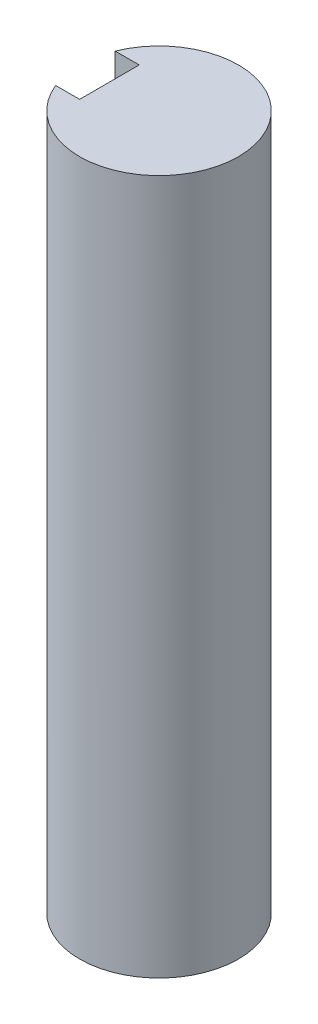
SolidWorks part; units mm, degrees
ref_plane "Front Plane" through (0, 0, 0) normal (0, 0, 1) x (1, 0, 0)
ref_plane "Top Plane" through (0, 0, 0) normal (0, 1, 0) x (1, 0, 0)
ref_plane "Right Plane" through (0, 0, 0) normal (1, 0, 0) x (0, 0, -1)
sketch "Sketch1" plane through (0, 0, 0) normal (0, 1, 0) x (1, 0, 0)
  circle A0 centre (0, 0) radius 4
  dimension "D1" = 8
extrude "Boss-Extrude1" add sketch "Sketch1" along normal blind 35
sketch "Sketch2" plane through (0, 0, 0) normal (0, -1, 0) x (1, 0, 0)
  line L0 (0, -2.5) -> (0, 2) construction
  line L1 (-1.5, 2) -> (1.5, 2)
  arc A0 (-1.5, 2) -> (1.5, 2) centre (0, 0) ccw
  dimension "D1" = 5
  dimension "D2" = 4.5
extrude "Cut-Extrude1" cut sketch "Sketch2" against normal blind 22
sketch "Sketch3" plane through (0, 0, 0) normal (0, -1, 0) x (1, 0, 0)
  circle A0 centre (0, 0) radius 2.5
  dimension "D1" = 5
extrude "Cut-Extrude2" cut sketch "Sketch3" against normal blind 4
sketch "Sketch4" plane through (0, 35, 0) normal (0, 1, 0) x (1, 0, 0)
  line L1 (-5.5, 1.5) -> (-2.5, 1.5)
  line L2 (-5.5, 1.5) -> (-5.5, -1.5)
  line L3 (-5.5, -1.5) -> (-2.5, -1.5)
  line L4 (-2.5, 1.5) -> (-2.5, -1.5)
  line L5 (-5.5, 1.5) -> (-2.5, -1.5) construction
  line L6 (-5.5, -1.5) -> (-2.5, 1.5) construction
  circle A0 centre (0, 0) radius 4 construction
  point P3 (-4, 0)
  dimension "D2" = 8
  dimension "D1" = 3
extrude "Cut-Extrude3" cut sketch "Sketch4" against normal blind 5
